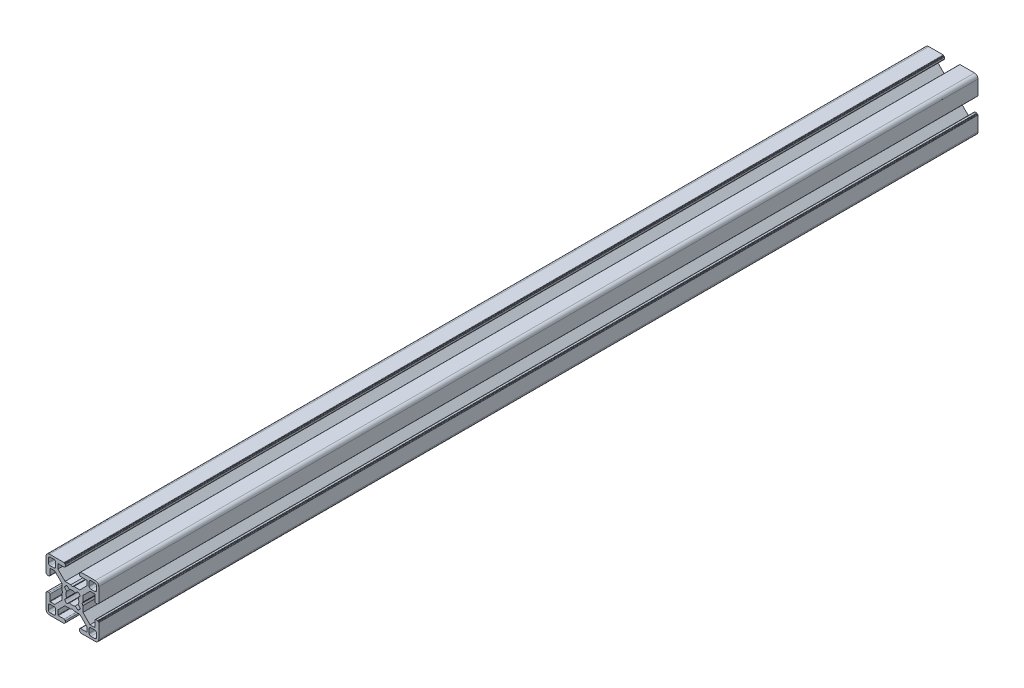
SolidWorks part; units mm, degrees
ref_plane "Płaszczyzna przednia" through (0, 0, 0) normal (0, 0, 1) x (1, 0, 0)
ref_plane "Płaszczyzna górna" through (0, 0, 0) normal (0, 1, 0) x (1, 0, 0)
ref_plane "Płaszczyzna prawa" through (0, 0, 0) normal (1, 0, 0) x (0, 0, -1)
sketch "Szkic1" plane through (0, 0, 0) normal (0, 0, 1) x (1, 0, 0)
  line L0 (109.26, 48.76) -> (107.06, 48.76)
  line L1 (106.06, 47.76) -> (106.06, 45.56)
  line L2 (107.06, 44.56) -> (109.26, 44.56)
  line L3 (110.26, 45.56) -> (110.26, 47.76)
  line L4 (94.9599, 38.3406) -> (93.4241, 39.5784)
  line L5 (92.0547, 38.2147) -> (93.2794, 36.6601)
  line L6 (93.2794, 33.4599) -> (92.0547, 31.9053)
  line L7 (93.4241, 30.5416) -> (94.9599, 31.7794)
  line L8 (98.1601, 31.7794) -> (99.6959, 30.5416)
  line L9 (101.0653, 31.9053) -> (99.8406, 33.4599)
  line L10 (99.8406, 36.6601) -> (101.0653, 38.2147)
  line L11 (99.6959, 39.5784) -> (98.1601, 38.3406)
  line L12 (83.86, 21.36) -> (86.06, 21.36)
  line L13 (87.06, 22.36) -> (87.06, 24.56)
  line L14 (86.06, 25.56) -> (83.86, 25.56)
  line L15 (82.86, 24.56) -> (82.86, 22.36)
  line L16 (110.26, 22.36) -> (110.26, 24.56)
  line L17 (109.26, 25.56) -> (107.06, 25.56)
  line L18 (106.06, 24.56) -> (106.06, 22.36)
  line L19 (86.06, 48.76) -> (83.86, 48.76)
  line L20 (82.86, 47.76) -> (82.86, 45.56)
  line L21 (83.86, 44.56) -> (86.06, 44.56)
  line L22 (87.06, 45.56) -> (87.06, 47.76)
  line L23 (107.06, 21.36) -> (109.26, 21.36)
  line L24 (96.56, 29.5751) -> (97.46, 29.06)
  line L25 (97.46, 29.06) -> (100.7645, 29.06)
  line L26 (100.7645, 29.06) -> (104.81, 25.01)
  line L27 (104.81, 25.01) -> (104.81, 22.46)
  line L28 (104.61, 22.26) -> (101.21, 22.26)
  line L29 (100.61, 21.66) -> (100.61, 20.76)
  line L30 (100.81, 20.56) -> (100.91, 20.56)
  line L31 (101.11, 20.36) -> (101.11, 20.26)
  line L32 (101.31, 20.06) -> (109.56, 20.06)
  line L33 (111.56, 22.06) -> (111.56, 30.31)
  line L34 (111.36, 30.51) -> (111.26, 30.51)
  line L35 (111.06, 30.71) -> (111.06, 30.81)
  line L36 (110.86, 31.01) -> (109.96, 31.01)
  line L37 (109.36, 30.41) -> (109.36, 27.01)
  line L38 (109.16, 26.81) -> (106.61, 26.81)
  line L39 (106.61, 26.81) -> (102.5645, 30.8555)
  line L40 (102.5645, 30.8555) -> (102.5645, 34.16)
  line L41 (102.5645, 34.16) -> (102.0449, 35.06)
  line L42 (102.0449, 35.06) -> (102.5645, 35.96)
  line L43 (102.5645, 35.96) -> (102.5645, 39.2645)
  line L44 (102.5645, 39.2645) -> (106.61, 43.31)
  line L45 (106.61, 43.31) -> (109.16, 43.31)
  line L46 (109.36, 43.11) -> (109.36, 39.71)
  line L47 (109.96, 39.11) -> (110.86, 39.11)
  line L48 (111.06, 39.31) -> (111.06, 39.41)
  line L49 (111.26, 39.61) -> (111.36, 39.61)
  line L50 (111.56, 39.81) -> (111.56, 48.06)
  line L51 (109.56, 50.06) -> (101.31, 50.06)
  line L52 (101.11, 49.86) -> (101.11, 49.76)
  line L53 (100.91, 49.56) -> (100.81, 49.56)
  line L54 (100.61, 49.36) -> (100.61, 48.46)
  line L55 (101.21, 47.86) -> (104.61, 47.86)
  line L56 (104.81, 47.66) -> (104.81, 45.11)
  line L57 (104.81, 45.11) -> (100.7645, 41.06)
  line L58 (100.7645, 41.06) -> (97.46, 41.06)
  line L59 (97.46, 41.06) -> (96.56, 40.5449)
  line L60 (96.56, 40.5449) -> (95.66, 41.06)
  line L61 (95.66, 41.06) -> (92.3555, 41.06)
  line L62 (92.3555, 41.06) -> (88.31, 45.11)
  line L63 (88.31, 45.11) -> (88.31, 47.66)
  line L64 (88.51, 47.86) -> (91.91, 47.86)
  line L65 (92.51, 48.46) -> (92.51, 49.36)
  line L66 (92.31, 49.56) -> (92.21, 49.56)
  line L67 (92.01, 49.76) -> (92.01, 49.86)
  line L68 (91.81, 50.06) -> (83.56, 50.06)
  line L69 (81.56, 48.06) -> (81.56, 39.81)
  line L70 (81.76, 39.61) -> (81.86, 39.61)
  line L71 (82.06, 39.41) -> (82.06, 39.31)
  line L72 (82.26, 39.11) -> (83.16, 39.11)
  line L73 (83.76, 39.71) -> (83.76, 43.11)
  line L74 (83.96, 43.31) -> (86.51, 43.31)
  line L75 (86.51, 43.31) -> (90.5555, 39.2645)
  line L76 (90.5555, 39.2645) -> (90.5555, 35.96)
  line L77 (90.5555, 35.96) -> (91.0751, 35.06)
  line L78 (91.0751, 35.06) -> (90.5555, 34.16)
  line L79 (90.5555, 34.16) -> (90.5555, 30.8555)
  line L80 (90.5555, 30.8555) -> (86.51, 26.81)
  line L81 (86.51, 26.81) -> (83.96, 26.81)
  line L82 (83.76, 27.01) -> (83.76, 30.41)
  line L83 (83.16, 31.01) -> (82.26, 31.01)
  line L84 (82.06, 30.81) -> (82.06, 30.71)
  line L85 (81.86, 30.51) -> (81.76, 30.51)
  line L86 (81.56, 30.31) -> (81.56, 22.06)
  line L87 (83.56, 20.06) -> (91.81, 20.06)
  line L88 (92.01, 20.26) -> (92.01, 20.36)
  line L89 (92.21, 20.56) -> (92.31, 20.56)
  line L90 (92.51, 20.76) -> (92.51, 21.66)
  line L91 (91.91, 22.26) -> (88.51, 22.26)
  line L92 (88.31, 22.46) -> (88.31, 25.01)
  line L93 (88.31, 25.01) -> (92.3555, 29.06)
  line L94 (92.3555, 29.06) -> (95.66, 29.06)
  line L95 (95.66, 29.06) -> (96.56, 29.5751)
  arc A0 (107.06, 48.76) -> (106.06, 47.76) centre (107.06, 47.76) ccw
  arc A1 (106.06, 45.56) -> (107.06, 44.56) centre (107.06, 45.56) ccw
  arc A2 (109.26, 44.56) -> (110.26, 45.56) centre (109.26, 45.56) ccw
  arc A3 (110.26, 47.76) -> (109.26, 48.76) centre (109.26, 47.76) ccw
  arc A4 (93.4241, 39.5784) -> (92.0547, 38.2147) centre (96.56, 35.06) ccw
  arc A5 (93.2794, 36.6601) -> (93.2794, 33.4599) centre (96.56, 35.06) ccw
  arc A6 (92.0547, 31.9053) -> (93.4241, 30.5416) centre (96.56, 35.06) ccw
  arc A7 (94.9599, 31.7794) -> (98.1601, 31.7794) centre (96.56, 35.06) ccw
  arc A8 (99.6959, 30.5416) -> (101.0653, 31.9053) centre (96.56, 35.06) ccw
  arc A9 (99.8406, 33.4599) -> (99.8406, 36.6601) centre (96.56, 35.06) ccw
  arc A10 (101.0653, 38.2147) -> (99.6959, 39.5784) centre (96.56, 35.06) ccw
  arc A11 (98.1601, 38.3406) -> (94.9599, 38.3406) centre (96.56, 35.06) ccw
  arc A12 (86.06, 21.36) -> (87.06, 22.36) centre (86.06, 22.36) ccw
  arc A13 (87.06, 24.56) -> (86.06, 25.56) centre (86.06, 24.56) ccw
  arc A14 (83.86, 25.56) -> (82.86, 24.56) centre (83.86, 24.56) ccw
  arc A15 (82.86, 22.36) -> (83.86, 21.36) centre (83.86, 22.36) ccw
  arc A16 (109.26, 21.36) -> (110.26, 22.36) centre (109.26, 22.36) ccw
  arc A17 (110.26, 24.56) -> (109.26, 25.56) centre (109.26, 24.56) ccw
  arc A18 (107.06, 25.56) -> (106.06, 24.56) centre (107.06, 24.56) ccw
  arc A19 (106.06, 22.36) -> (107.06, 21.36) centre (107.06, 22.36) ccw
  arc A20 (83.86, 48.76) -> (82.86, 47.76) centre (83.86, 47.76) ccw
  arc A21 (82.86, 45.56) -> (83.86, 44.56) centre (83.86, 45.56) ccw
  arc A22 (86.06, 44.56) -> (87.06, 45.56) centre (86.06, 45.56) ccw
  arc A23 (87.06, 47.76) -> (86.06, 48.76) centre (86.06, 47.76) ccw
  arc A24 (104.61, 22.26) -> (104.81, 22.46) centre (104.61, 22.46) ccw
  arc A25 (101.21, 22.26) -> (100.61, 21.66) centre (101.21, 21.66) ccw
  arc A26 (100.61, 20.76) -> (100.81, 20.56) centre (100.81, 20.76) ccw
  arc A27 (101.11, 20.36) -> (100.91, 20.56) centre (100.91, 20.36) ccw
  arc A28 (101.11, 20.26) -> (101.31, 20.06) centre (101.31, 20.26) ccw
  arc A29 (109.56, 20.06) -> (111.56, 22.06) centre (109.56, 22.06) ccw
  arc A30 (111.56, 30.31) -> (111.36, 30.51) centre (111.36, 30.31) ccw
  arc A31 (111.06, 30.71) -> (111.26, 30.51) centre (111.26, 30.71) ccw
  arc A32 (111.06, 30.81) -> (110.86, 31.01) centre (110.86, 30.81) ccw
  arc A33 (109.96, 31.01) -> (109.36, 30.41) centre (109.96, 30.41) ccw
  arc A34 (109.16, 26.81) -> (109.36, 27.01) centre (109.16, 27.01) ccw
  arc A35 (109.36, 43.11) -> (109.16, 43.31) centre (109.16, 43.11) ccw
  arc A36 (109.36, 39.71) -> (109.96, 39.11) centre (109.96, 39.71) ccw
  arc A37 (110.86, 39.11) -> (111.06, 39.31) centre (110.86, 39.31) ccw
  arc A38 (111.26, 39.61) -> (111.06, 39.41) centre (111.26, 39.41) ccw
  arc A39 (111.36, 39.61) -> (111.56, 39.81) centre (111.36, 39.81) ccw
  arc A40 (111.56, 48.06) -> (109.56, 50.06) centre (109.56, 48.06) ccw
  arc A41 (101.31, 50.06) -> (101.11, 49.86) centre (101.31, 49.86) ccw
  arc A42 (100.91, 49.56) -> (101.11, 49.76) centre (100.91, 49.76) ccw
  arc A43 (100.81, 49.56) -> (100.61, 49.36) centre (100.81, 49.36) ccw
  arc A44 (100.61, 48.46) -> (101.21, 47.86) centre (101.21, 48.46) ccw
  arc A45 (104.81, 47.66) -> (104.61, 47.86) centre (104.61, 47.66) ccw
  arc A46 (88.51, 47.86) -> (88.31, 47.66) centre (88.51, 47.66) ccw
  arc A47 (91.91, 47.86) -> (92.51, 48.46) centre (91.91, 48.46) ccw
  arc A48 (92.51, 49.36) -> (92.31, 49.56) centre (92.31, 49.36) ccw
  arc A49 (92.01, 49.76) -> (92.21, 49.56) centre (92.21, 49.76) ccw
  arc A50 (92.01, 49.86) -> (91.81, 50.06) centre (91.81, 49.86) ccw
  arc A51 (83.56, 50.06) -> (81.56, 48.06) centre (83.56, 48.06) ccw
  arc A52 (81.56, 39.81) -> (81.76, 39.61) centre (81.76, 39.81) ccw
  arc A53 (82.06, 39.41) -> (81.86, 39.61) centre (81.86, 39.41) ccw
  arc A54 (82.06, 39.31) -> (82.26, 39.11) centre (82.26, 39.31) ccw
  arc A55 (83.16, 39.11) -> (83.76, 39.71) centre (83.16, 39.71) ccw
  arc A56 (83.96, 43.31) -> (83.76, 43.11) centre (83.96, 43.11) ccw
  arc A57 (83.76, 27.01) -> (83.96, 26.81) centre (83.96, 27.01) ccw
  arc A58 (83.76, 30.41) -> (83.16, 31.01) centre (83.16, 30.41) ccw
  arc A59 (82.26, 31.01) -> (82.06, 30.81) centre (82.26, 30.81) ccw
  arc A60 (81.86, 30.51) -> (82.06, 30.71) centre (81.86, 30.71) ccw
  arc A61 (81.76, 30.51) -> (81.56, 30.31) centre (81.76, 30.31) ccw
  arc A62 (81.56, 22.06) -> (83.56, 20.06) centre (83.56, 22.06) ccw
  arc A63 (91.81, 20.06) -> (92.01, 20.26) centre (91.81, 20.26) ccw
  arc A64 (92.21, 20.56) -> (92.01, 20.36) centre (92.21, 20.36) ccw
  arc A65 (92.31, 20.56) -> (92.51, 20.76) centre (92.31, 20.76) ccw
  arc A66 (92.51, 21.66) -> (91.91, 22.26) centre (91.91, 21.66) ccw
  arc A67 (88.31, 22.46) -> (88.51, 22.26) centre (88.51, 22.46) ccw
  dimension "D1" = 3.65
  dimension "D2" = 30
  dimension "D3" = 30
  dimension "D4" = 8.1
extrude "Dodanie-wyciągnięcie1" add sketch "Szkic1" along normal blind 500
